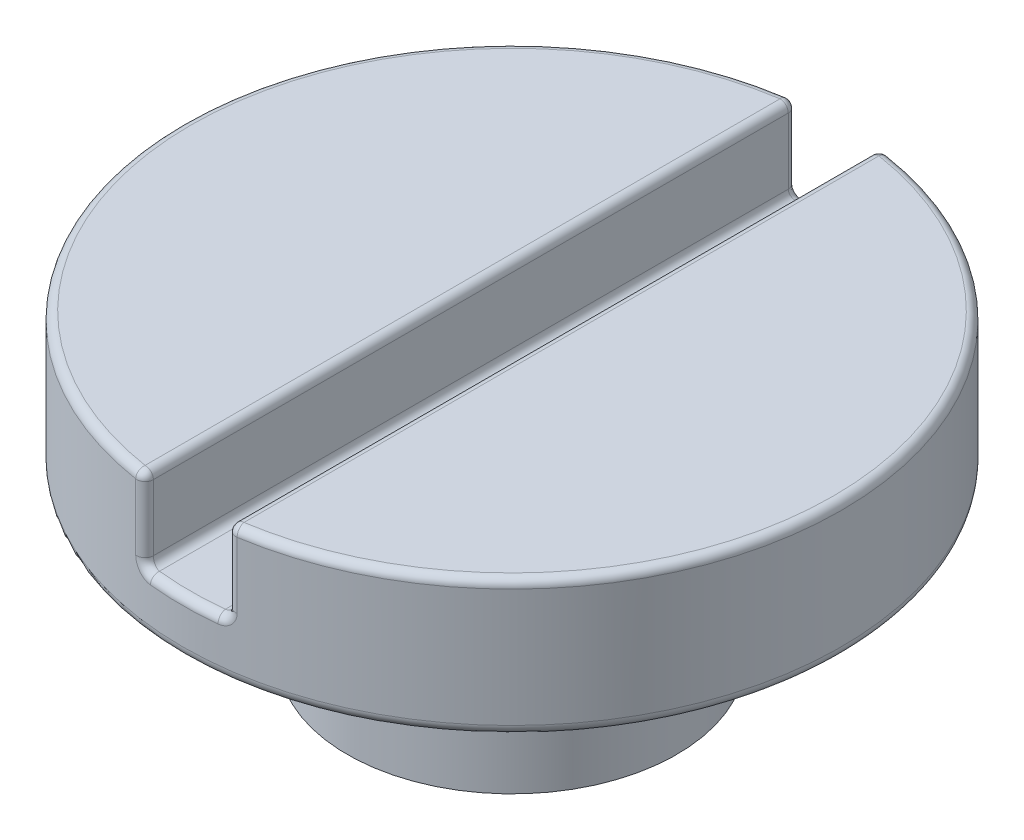
SolidWorks part; units mm, degrees
ref_plane "Front Plane" through (0, 0, 0) normal (1, 0, 0) x (0, 1, 0)
ref_plane "Top Plane" through (0, 0, 0) normal (0, 0, 1) x (0, 1, 0)
ref_plane "Right Plane" through (0, 0, 0) normal (0, 1, 0) x (-1, 0, 0)
sketch "Sketch2" plane through (0, 0, 0) normal (0, 1, 0) x (-1, 0, 0)
  circle A0 centre (0, 0) radius 60
  dimension "D1" = 120
extrude "Boss-Extrude1" add sketch "Sketch2" along normal blind 25
sketch "Sketch3" plane through (0, 0, 0) normal (0, -1, 0) x (1, 0, 0)
  circle A0 centre (0, 0) radius 30
  dimension "D1" = 60
extrude "Boss-Extrude2" add sketch "Sketch3" along normal blind 30
sketch "Sketch4" plane through (0, -30, 0) normal (0, -1, 0) x (1, 0, 0)
  circle A0 centre (0, 0) radius 15
extrude "Cut-Extrude1" cut sketch "Sketch4" against normal blind 30
sketch "Sketch5" plane through (0, -30, 0) normal (0, -1, 0) x (1, 0, 0)
  line L1 (-5, 19) -> (5, 19)
  line L2 (-5, 19) -> (-5, 11)
  line L3 (-5, 11) -> (5, 11)
  line L4 (5, 19) -> (5, 11)
  line L5 (-5, 19) -> (5, 11) construction
  line L6 (-5, 11) -> (5, 19) construction
  circle A0 centre (0, 0) radius 15 construction
  circle A1 centre (0, 0) radius 15 construction
  point P0 (0, 15)
  point P9 (0, 0)
  dimension "D1" = 10
  dimension "D2" = 8
extrude "Cut-Extrude2" cut sketch "Sketch5" against normal up to surface (30 mm away) up to face at (0, 0, -15)
sketch "Sketch6" plane through (0, 25, 0) normal (0, 1, 0) x (-1, 0, 0)
  line L1 (-7.5, -65) -> (7.5, -65)
  line L2 (-7.5, -65) -> (-7.5, 65)
  line L3 (-7.5, 65) -> (7.5, 65)
  line L4 (7.5, -65) -> (7.5, 65)
  line L5 (-7.5, -65) -> (7.5, 65) construction
  line L6 (-7.5, 65) -> (7.5, -65) construction
  point P0 (0, 0)
  dimension "D1" = 15
  dimension "D2" = 130
extrude "Cut-Extrude3" cut sketch "Sketch6" against normal blind 15
fillet "Fillet1" radius 2 1 edges at (0, 0, 60)
fillet "Fillet2" radius 1.5 12 edges at (7.5, 17.5, -59.5294) (7.5, 17.5, 59.5294) (-7.5, 17.5, 59.5294) (-7.5, 17.5, -59.5294) (0, 10, 60) (0, 10, -60) (-7.5, 10, 0) (7.5, 10, 0) (60, 25, 0) (7.5, 25, 0) (-60, 25, 0) (-7.5, 25, 0)
